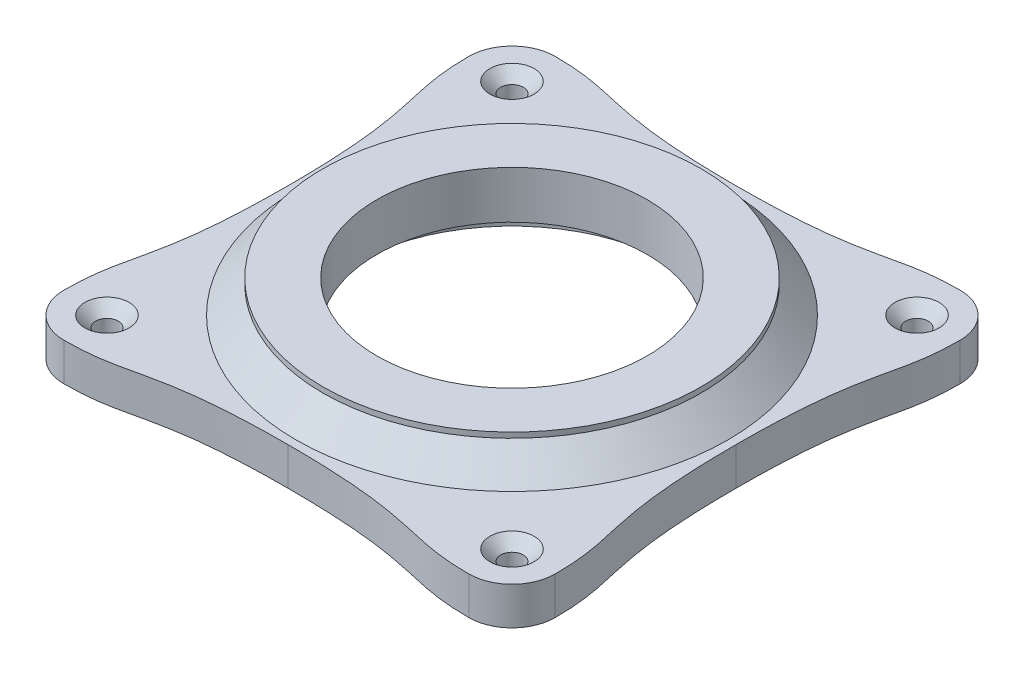
SolidWorks part; units mm, degrees
ref_plane "Front Plane" through (0, 0, 0) normal (0, 0, 1) x (1, 0, 0)
ref_plane "Top Plane" through (0, 0, 0) normal (0, 1, 0) x (1, 0, 0)
ref_plane "Right Plane" through (0, 0, 0) normal (1, 0, 0) x (0, 0, -1)
sketch "Sketch1" plane through (0, 0, 0) normal (0, 1, 0) x (1, 0, 0)
  line L0 (0, 75) -> (75, 0) construction
  line L1 (0, 0) -> (75, 0) construction
  line L2 (0, 0) -> (0, 75) construction
  line L3 (0, 75) -> (75, 75) construction
  line L4 (75, 0) -> (75, 75) construction
  line L5 (0, 75) -> (0, 93.0382) construction
  line L6 (0, 75) -> (-26.3477, 75) construction
  line L7 (75, 75) -> (75, 94.5096) construction
  line L8 (75, 75) -> (107.0147, 75) construction
  line L9 (37.5, 75) -> (37.5, 96.1148) construction
  line L10 (0, 79) -> (75, 79) construction
  line L11 (75, 83) -> (62.5, 83) construction
  line L12 (0, 83) -> (12.5, 83) construction
  line L13 (12.5, 83) -> (12.5, 79) construction
  line L14 (12.5, 79) -> (37.5, 79) construction
  line L15 (62.5, 83) -> (62.5, 79) construction
  line L16 (62.5, 79) -> (37.5, 79) construction
  line L17 (83, 0) -> (83, 12.5) construction
  line L18 (83, 75) -> (83, 62.5) construction
  line L19 (83, 62.5) -> (79, 62.5) construction
  line L20 (79, 62.5) -> (79, 37.5) construction
  line L21 (83, 12.5) -> (79, 12.5) construction
  line L22 (79, 12.5) -> (79, 37.5) construction
  line L23 (0, -8) -> (12.5, -8) construction
  line L24 (75, -8) -> (62.5, -8) construction
  line L25 (62.5, -8) -> (62.5, -4) construction
  line L26 (62.5, -4) -> (37.5, -4) construction
  line L27 (12.5, -8) -> (12.5, -4) construction
  line L28 (12.5, -4) -> (37.5, -4) construction
  line L29 (-8, 75) -> (-8, 62.5) construction
  line L30 (-8, 0) -> (-8, 12.5) construction
  line L31 (-8, 12.5) -> (-4, 12.5) construction
  line L32 (-4, 12.5) -> (-4, 37.5) construction
  line L33 (-8, 62.5) -> (-4, 62.5) construction
  line L34 (-4, 62.5) -> (-4, 37.5) construction
  circle A0 centre (0, 75) radius 2.1
  circle A1 centre (75, 75) radius 2.1
  circle A2 centre (75, 0) radius 2.1
  circle A3 centre (0, 0) radius 2.1
  arc A4 (0, 83) -> (-8, 75) centre (0, 75) ccw
  arc A5 (83, 75) -> (75, 83) centre (75, 75) ccw
  arc A6 (83, 75) -> (75, 83) centre (75, 75) ccw
  arc A7 (75, -8) -> (83, 0) centre (75, 0) ccw
  arc A8 (75, -8) -> (83, 0) centre (75, 0) ccw
  arc A9 (-8, 0) -> (0, -8) centre (0, 0) ccw
  arc A10 (-8, 0) -> (0, -8) centre (0, 0) ccw
  arc A11 (0, 83) -> (-8, 75) centre (0, 75) ccw
  circle A12 centre (37.5, 37.5) radius 25.05
  spline S0 degree 3 poles (0, 83) (12.5, 83) (12.5, 79) (37.5, 79) knots 0 0 0 0 1 1 1 1
  spline S1 degree 3 poles (75, 83) (62.5, 83) (62.5, 79) (37.5, 79) knots 0 0 0 0 1 1 1 1
  spline S2 degree 3 poles (83, 75) (83, 62.5) (79, 62.5) (79, 37.5) knots 0 0 0 0 1 1 1 1
  spline S3 degree 3 poles (83, 0) (83, 12.5) (79, 12.5) (79, 37.5) knots 0 0 0 0 1 1 1 1
  spline S4 degree 3 poles (75, -8) (62.5, -8) (62.5, -4) (37.5, -4) knots 0 0 0 0 1 1 1 1
  spline S5 degree 3 poles (0, -8) (12.5, -8) (12.5, -4) (37.5, -4) knots 0 0 0 0 1 1 1 1
  spline S6 degree 3 poles (-8, 0) (-8, 12.5) (-4, 12.5) (-4, 37.5) knots 0 0 0 0 1 1 1 1
  spline S7 degree 3 poles (-8, 75) (-8, 62.5) (-4, 62.5) (-4, 37.5) knots 0 0 0 0 1 1 1 1
  point P25 (37.5, 37.5)
  point P63 (37.5, 37.5)
  dimension "D2" = 4.2
  dimension "D3" = 8
  dimension "D4" = 4
  dimension "D6" = 50.1
  dimension "D1" = 75
  dimension "D5" = 25
  dimension "D7" = 4
extrude "Boss-Extrude1" add sketch "Sketch1" along normal blind 7 contours A4 S7 S6 A9 S5 S4 A7 S3 S2 A5 S1 S0 A0 A1 A2 A3
sketch "Sketch5" plane through (0, 0, 0) normal (0, -1, 0) x (1, 0, 0)
  circle A0 centre (37.5, -37.5) radius 25.05 construction
  circle A1 centre (37.5, -37.5) radius 25.05
  circle A2 centre (37.5, -37.5) radius 30.1
  dimension "D1" = 60.2
extrude "Cut-Extrude1" cut sketch "Sketch5" against normal blind 4.2
sketch "Sketch6" plane through (0, 7, 0) normal (0, 1, 0) x (1, 0, 0)
  circle A0 centre (37.5, 37.5) radius 25.05 construction
  circle A1 centre (37.5, 37.5) radius 25.05
  circle A2 centre (37.5, 37.5) radius 35
  dimension "D1" = 70
extrude "Boss-Extrude4" add sketch "Sketch6" along normal blind 6
chamfer "Chamfer1" distance 2 angle 45 4 edges at (0, 7, -72.9) (0, 7, 2.1) (75, 7, 2.1) (75, 7, -72.9)
chamfer "Chamfer2" distance 5 angle 45 1 edges at (37.5, 7, -2.5)
